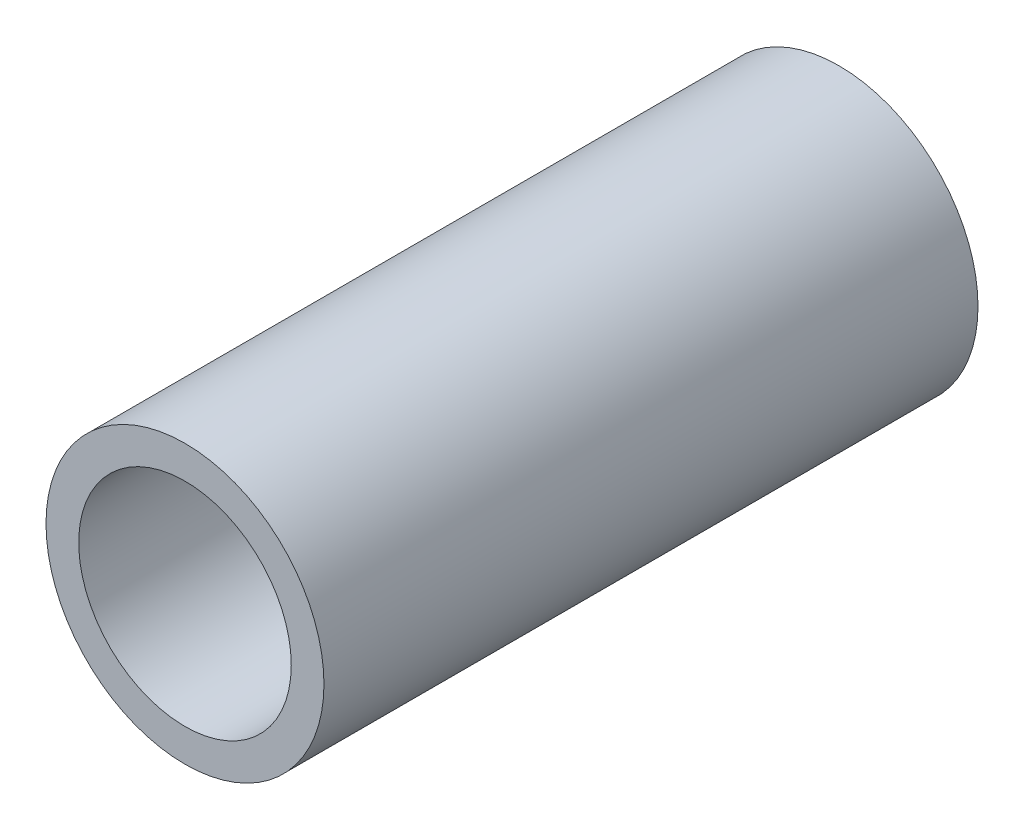
SolidWorks part; units mm, degrees
ref_plane "前视基准面" through (0, 0, 0) normal (0, 0, 1) x (1, 0, 0)
ref_plane "上视基准面" through (0, 0, 0) normal (0, 1, 0) x (1, 0, 0)
ref_plane "右视基准面" through (0, 0, 0) normal (1, 0, 0) x (0, 0, -1)
sketch "草图1" plane through (0, 0, 0) normal (0, 0, 1) x (1, 0, 0)
  circle A0 centre (0, 0) radius 17
  circle A1 centre (0, 0) radius 13
  dimension "D1" = 34
  dimension "D2" = 26
extrude "拉伸1" add sketch "草图1" along normal blind 80
